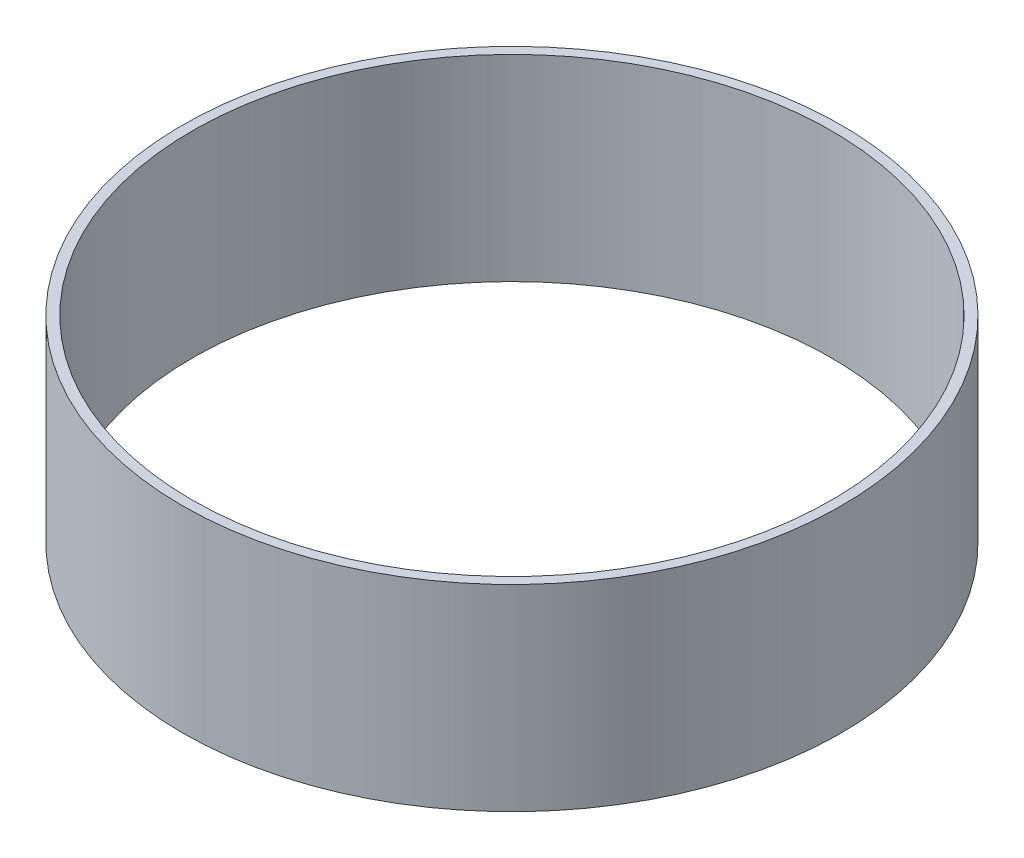
SolidWorks part; units mm, degrees
ref_plane "Front Plane" through (0, 0, 0) normal (0, 0, 1) x (1, 0, 0)
ref_plane "Top Plane" through (0, 0, 0) normal (0, 1, 0) x (1, 0, 0)
ref_plane "Right Plane" through (0, 0, 0) normal (1, 0, 0) x (0, 0, -1)
sketch "Sketch1" plane through (0, 0, 0) normal (0, 1, 0) x (1, 0, 0)
  circle A0 centre (0, 0) radius 5105.4
  circle A1 centre (0, 0) radius 4953
  dimension "D1" = 152.4
  dimension "D2" = 10210.8
extrude "Boss-Extrude1" add sketch "Sketch1" along normal blind 3048
